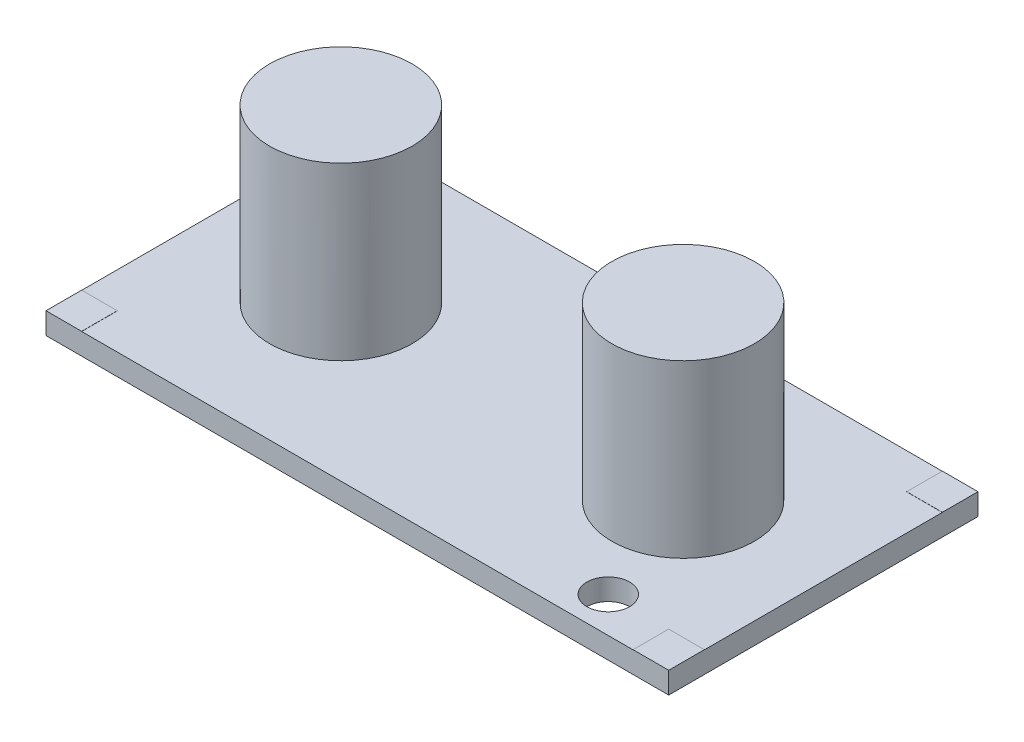
SolidWorks part; units mm, degrees
ref_plane "Front Plane" through (0, 0, 0) normal (0, 0, 1) x (1, 0, 0)
ref_plane "Top Plane" through (0, 0, 0) normal (0, 1, 0) x (1, 0, 0)
ref_plane "Right Plane" through (0, 0, 0) normal (1, 0, 0) x (0, 0, -1)
sketch "Sketch1" plane through (0, 0, 0) normal (0, 1, 0) x (1, 0, 0)
  line L1 (-21.835, -10.845) -> (21.835, -10.845)
  line L2 (-21.835, -10.845) -> (-21.835, 10.845)
  line L3 (-21.835, 10.845) -> (21.835, 10.845)
  line L4 (21.835, -10.845) -> (21.835, 10.845)
  line L5 (-21.835, -10.845) -> (21.835, 10.845) construction
  line L6 (-21.835, 10.845) -> (21.835, -10.845) construction
  circle A0 centre (-15.145, 8.035) radius 1.5
  circle A1 centre (15.095, -8.345) radius 1.5
  point P0 (0, 0)
  dimension "D3" = 3
  dimension "D5" = 2.81
  dimension "D6" = 2.5
  dimension "D7" = 6.74
  dimension "D1" = 21.69
  dimension "D2" = 43.67
  dimension "D4" = 6.69
extrude "Boss-Extrude1" add sketch "Sketch1" along normal blind 1.5
sketch "Sketch2" plane through (0, 1.5, 0) normal (0, 1, 0) x (1, 0, 0)
  line L1 (-21.835, 10.845) -> (-19.335, 10.845)
  line L2 (-21.835, 10.845) -> (-21.835, 8.345)
  line L3 (-21.835, 8.345) -> (-19.335, 8.345)
  line L4 (-19.335, 10.845) -> (-19.335, 8.345)
  line L5 (-21.835, -10.845) -> (-19.335, -10.845)
  line L6 (-21.835, -10.845) -> (-21.835, -8.345)
  line L7 (-21.835, -8.345) -> (-19.335, -8.345)
  line L8 (-19.335, -10.845) -> (-19.335, -8.345)
  dimension "D1" = 2.5
extrude "Boss-Extrude2" add sketch "Sketch2" along normal blind 0.01
sketch "Sketch3" plane through (0, 1.5, 0) normal (0, 1, 0) x (1, 0, 0)
  line L1 (21.835, 10.845) -> (19.335, 10.845)
  line L2 (21.835, 10.845) -> (21.835, 8.345)
  line L3 (21.835, 8.345) -> (19.335, 8.345)
  line L4 (19.335, 10.845) -> (19.335, 8.345)
  line L5 (21.835, -10.845) -> (19.335, -10.845)
  line L6 (21.835, -10.845) -> (21.835, -8.345)
  line L7 (21.835, -8.345) -> (19.335, -8.345)
  line L8 (19.335, -10.845) -> (19.335, -8.345)
  dimension "D1" = 2.5
extrude "Boss-Extrude3" add sketch "Sketch3" along normal blind 0.01
sketch "Sketch4" plane through (0, 1.5, 0) normal (0, 1, 0) x (1, 0, 0)
  line L0 (0, -0.8305) -> (0, 0.8305) construction
  circle A0 centre (-12, 0) radius 5
  circle A1 centre (12, 0) radius 5
  point P2 (0, 0)
  dimension "D1" = 10
  dimension "D2" = 12
extrude "Boss-Extrude4" add sketch "Sketch4" along normal blind 12
